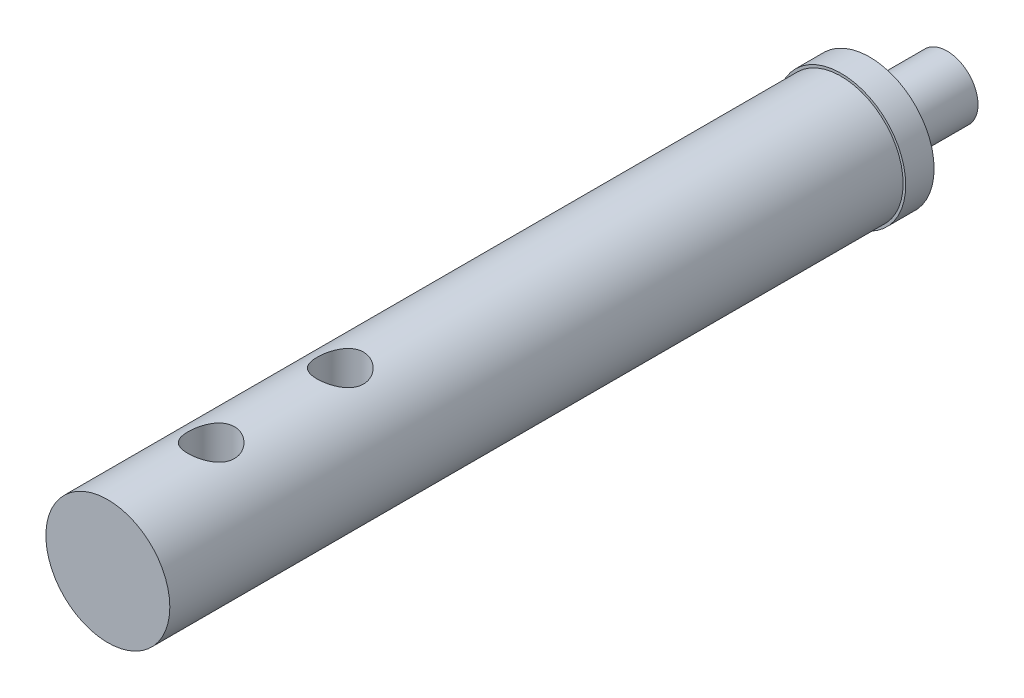
SolidWorks part; units mm, degrees
material "ASTM A36 Steel"
ref_plane "Front Plane" through (0, 0, 0) normal (0, 0, 1) x (1, 0, 0)
ref_plane "Top Plane" through (0, 0, 0) normal (0, 1, 0) x (1, 0, 0)
ref_plane "Right Plane" through (0, 0, 0) normal (1, 0, 0) x (0, 0, -1)
sketch "Sketch1" plane through (0, 0, 0) normal (0, 0, 1) x (1, 0, 0)
  circle A0 centre (0, 0) radius 6
  dimension "D1" = 12
extrude "Boss-Extrude1" add sketch "Sketch1" along normal blind 15
sketch "Sketch2" plane through (0, 0, 15) normal (0, 0, 1) x (1, 0, 0)
  circle A0 centre (0, 0) radius 12.5
  dimension "D1" = 25
extrude "Boss-Extrude2" add sketch "Sketch2" along normal blind 5.5
sketch "Sketch3" plane through (0, 0, 20.5) normal (0, 0, 1) x (1, 0, 0)
  circle A0 centre (0, 0) radius 12
  dimension "D1" = 24
extrude "Boss-Extrude3" add sketch "Sketch3" along normal blind 142
sketch "Sketch4" plane through (0, 0, 0) normal (0, 1, 0) x (1, 0, 0)
  line L0 (-12, -162.5) -> (12, -162.5) construction
  circle A0 centre (0, -142.5) radius 4.5
  dimension "D1" = 9
  dimension "D2" = 20
extrude "Cut-Extrude1" cut sketch "Sketch4" against normal through all both and the other way through all
pattern_linear "LPattern1" count 2 spacing 25 along (0, 0, -1) of "Cut-Extrude1"
